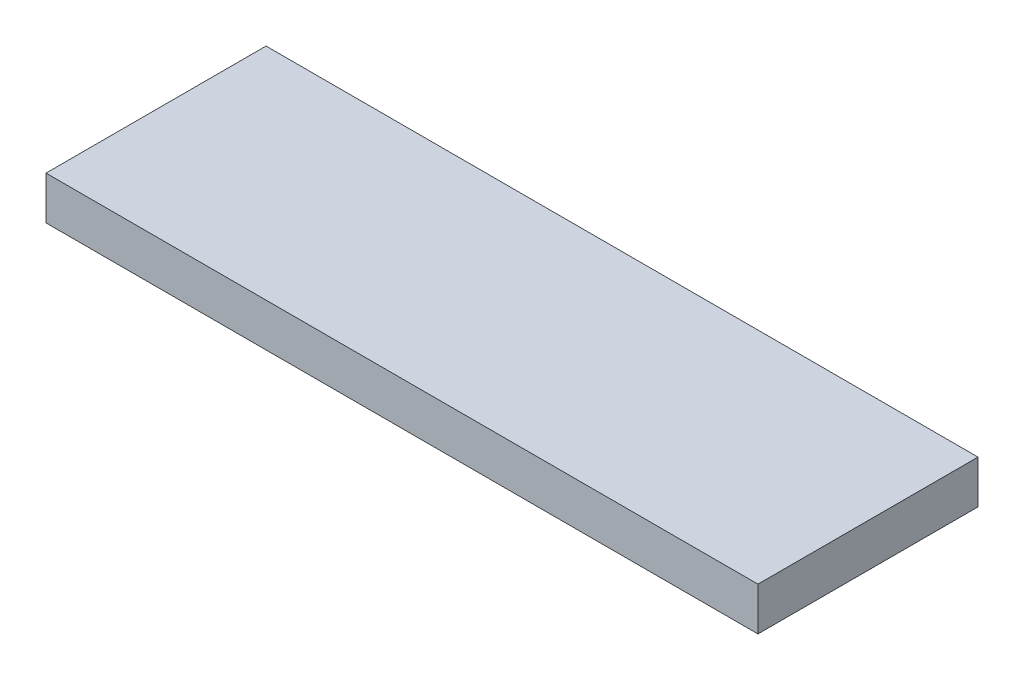
SolidWorks part; units mm, degrees
ref_plane "Front Plane" through (0, 0, 0) normal (0, 0, 1) x (1, 0, 0)
ref_plane "Top Plane" through (0, 0, 0) normal (0, 1, 0) x (1, 0, 0)
ref_plane "Right Plane" through (0, 0, 0) normal (1, 0, 0) x (0, 0, -1)
sketch "Sketch1" plane through (0, 0, 0) normal (0, 1, 0) x (1, 0, 0)
  line L6 (-55.1823, -20.6706) -> (10.8177, -20.6706)
  line L14 (-55.1823, -20.6706) -> (-55.1823, -41.0706)
  line L19 (-55.1823, -41.0706) -> (10.8177, -41.0706)
  line L20 (10.8177, -20.6706) -> (10.8177, -41.0706)
  dimension "D3" = 66
  dimension "D4" = 20.4
extrude "Boss-Extrude1" add sketch "Sketch1" along normal mid plane 4
equation "\"wall_thick_nes\"=4"
equation "\"D1@Boss-Extrude1\"=\"wall_thick_nes\""
